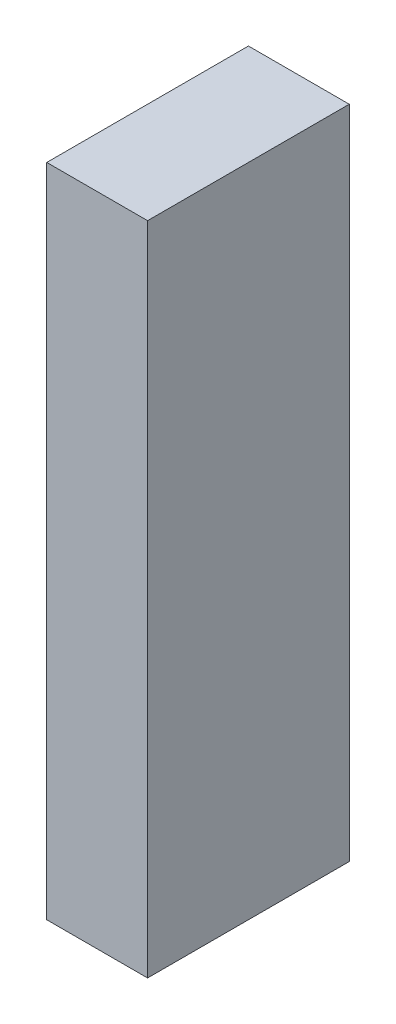
SolidWorks part; units mm, degrees
ref_plane "Front Plane" through (0, 0, 0) normal (0, 0, 1) x (1, 0, 0)
ref_plane "Top Plane" through (0, 0, 0) normal (0, 1, 0) x (1, 0, 0)
ref_plane "Right Plane" through (0, 0, 0) normal (1, 0, 0) x (0, 0, -1)
sketch "Sketch1" plane through (0, 0, 0) normal (0, 0, 1) x (1, 0, 0)
  line L48 (47.8539, 133.2285) -> (47.8539, 68.1821)
  line L49 (47.8539, 68.1821) -> (57.8539, 68.1821)
  line L50 (57.8539, 68.1821) -> (57.8539, 133.2285)
  line L51 (57.8539, 133.2285) -> (47.8539, 133.2285)
extrude "Boss-Extrude1" add sketch "Sketch1" along normal blind 20 contours L50 L51 L48 L49
